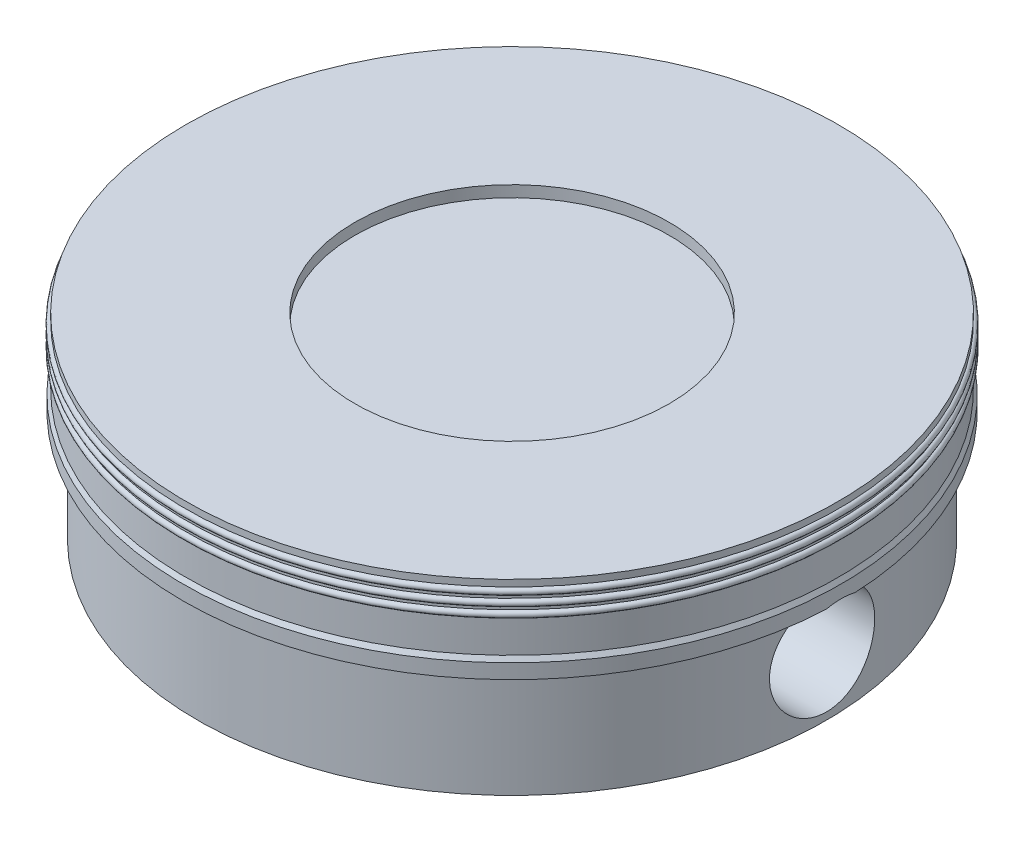
SolidWorks part; units mm, degrees
ref_plane "Front Plane" through (0, 0, 0) normal (0, 0, 1) x (1, 0, 0)
ref_plane "Top Plane" through (0, 0, 0) normal (0, 1, 0) x (1, 0, 0)
ref_plane "Right Plane" through (0, 0, 0) normal (1, 0, 0) x (0, 0, -1)
sketch "Sketch2" plane through (0, 0, 0) normal (0, 0, 1) x (1, 0, 0)
  line L0 (-4.5703, -0.7529) -> (-4.5703, -2.972) construction
  line L1 (-4.5703, -2.972) -> (0.4297, -2.972) construction
  line L2 (0.2097, -2.972) -> (-1.1403, -2.972)
  line L3 (-1.1403, -2.972) -> (-1.1403, -1.042)
  line L4 (-1.1403, -1.042) -> (0, -1.042)
  line L5 (0, -1.042) -> (0, -0.642)
  line L6 (0, -0.642) -> (-4.5703, -0.642)
  line L7 (-4.5703, -0.642) -> (-4.5703, -0.172)
  line L8 (-4.5703, -0.172) -> (-2.1803, -0.172)
  line L9 (-2.1803, -0.172) -> (-2.1803, 0)
  line L10 (-2.1803, 0) -> (0.3897, 0)
  line L11 (0.3897, 0) -> (0.3897, -0.1)
  line L12 (0.3897, -1) -> (0.4297, -1.07)
  line L13 (0.4297, -1.07) -> (0.4297, -1.292)
  line L14 (0.4297, -1.292) -> (0.2097, -1.292)
  line L15 (0.2097, -1.292) -> (0.2097, -2.972)
  line L16 (0.3897, -0.2) -> (0.3897, -0.25)
  line L17 (0.3897, -0.35) -> (0.3897, -0.4)
  line L18 (0.3897, -0.5) -> (0.3897, -1)
  arc A0 (0.3897, -0.2) -> (0.3897, -0.1) centre (0.3897, -0.15) ccw
  arc A1 (0.3897, -0.35) -> (0.3897, -0.25) centre (0.3897, -0.3) ccw
  arc A2 (0.3897, -0.5) -> (0.3897, -0.4) centre (0.3897, -0.45) ccw
  point P10 (0.4297, -1.181)
  dimension "D16" = 0.1
  dimension "D17" = 0.1
  dimension "D18" = 0.1
  dimension "D2" = 5
  dimension "D3" = 4.96
  dimension "D4" = 0.04
  dimension "D5" = 1.68
  dimension "D6" = 0.22
  dimension "D7" = 1.35
  dimension "D8" = 1.93
  dimension "D9" = 0.4
  dimension "D10" = 2.57
  dimension "D11" = 0.172
  dimension "D12" = 0.47
  dimension "D13" = 0.15
  dimension "D14" = 0.15
  dimension "D15" = 0.15
  dimension "D19" = 0.07
  dimension "D20" = 1
revolve "Revolve2" add sketch "Sketch2" angle 360 about L0
sketch "Sketch3" plane through (0, -2.972, 0) normal (0, -1, 0) x (1, 0, 0)
  line L0 (-4.5703, 0) -> (-4.5703, 3.43) construction
  line L1 (-4.5703, 0) -> (-8.0003, 0) construction
  line L2 (-6.0703, 3.0846) -> (-6.0703, -3.0846)
  line L3 (-3.0703, 3.0846) -> (-3.0703, -3.0846)
  circle A0 centre (-4.5703, 0) radius 3.43 construction
  arc A1 (-6.0703, 3.0846) -> (-6.0703, -3.0846) centre (-4.5703, 0) ccw
  arc A2 (-3.0703, -3.0846) -> (-3.0703, 3.0846) centre (-4.5703, 0) ccw
  point P12 (0, 0)
  dimension "D1" = 1.5
  dimension "D2" = 3
extrude "Boss-Extrude1" add sketch "Sketch3" against normal up to surface (2.33 mm away) separate body up to face at (-9.1406, -0.642, 0)
sketch "Sketch4" plane through (0, 0, 0) normal (1, 0, 0) x (0, 0, -1)
  line L0 (-4.78, -2.972) -> (4.78, -2.972) construction
  circle A0 centre (0, -2.062) radius 0.8
  dimension "D1" = 1.6
  dimension "D2" = 0.91
extrude "Cut-Extrude1" cut sketch "Sketch4" against normal through all both and the other way through all
